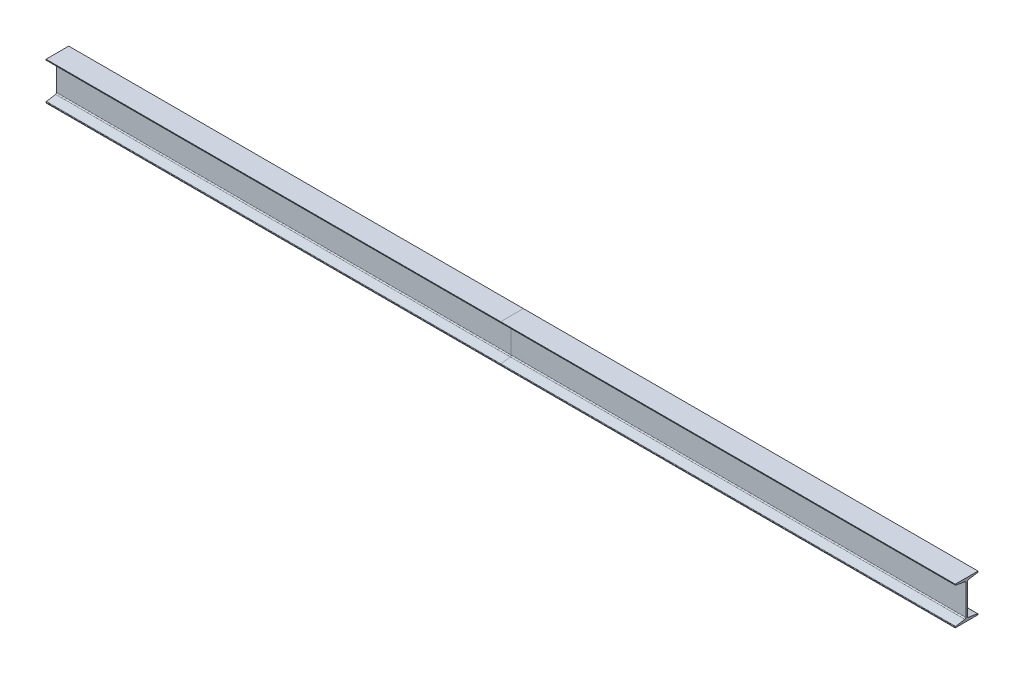
SolidWorks part; units mm, degrees
ref_plane "Front Plane" through (0, 0, 0) normal (0, 0, 1) x (1, 0, 0)
ref_plane "Top Plane" through (0, 0, 0) normal (0, 1, 0) x (1, 0, 0)
ref_plane "Right Plane" through (0, 0, 0) normal (1, 0, 0) x (0, 0, -1)
sketch "Sketch1" plane through (0, 0, 0) normal (0, 0, 1) x (1, 0, 0)
  line L0 (0, 0) -> (3048, 0)
  line L1 (3048, 0) -> (6096, 0)
  point P3 (4572, 0)
  dimension "D1" = 3048
  dimension "D2" = 6096
other "Structural Member1"
ref_plane "Plane1" through (0, 0, 0) normal (1, 0, 0) x (0, 0, 1)
sketch "Sketch11" plane through (0, 0, 0) normal (1, 0, 0) x (0, 0, 1)
  line L0 (-76.2, -127) -> (-76.2, -122.8792)
  line L1 (-73.4409, -119.6222) -> (-11.9134, -109.3669)
  line L2 (-5.334, -101.6) -> (-5.334, 101.6)
  line L3 (-11.9134, 109.3669) -> (-73.4409, 119.6222)
  line L4 (-76.2, 122.8792) -> (-76.2, 127)
  line L5 (-76.2, 127) -> (76.2, 127)
  line L6 (76.2, 127) -> (76.2, 122.8792)
  line L7 (73.4409, 119.6222) -> (11.9134, 109.3669)
  line L8 (5.334, 101.6) -> (5.334, -101.6)
  line L9 (11.9134, -109.3669) -> (73.4409, -119.6222)
  line L10 (76.2, -122.8792) -> (76.2, -127)
  line L11 (76.2, -127) -> (-76.2, -127)
  line L15 (-5.334, 0) -> (5.334, 0) construction
  arc A0 (-11.9134, -109.3669) -> (-5.334, -101.6) centre (-13.208, -101.6) ccw
  arc A1 (-5.334, 101.6) -> (-11.9134, 109.3669) centre (-13.208, 101.6) ccw
  arc A2 (11.9134, 109.3669) -> (5.334, 101.6) centre (13.208, 101.6) ccw
  arc A3 (5.334, -101.6) -> (11.9134, -109.3669) centre (13.208, -101.6) ccw
  arc A4 (-73.4409, 119.6222) -> (-76.2, 122.8792) centre (-72.898, 122.8792) cw
  arc A5 (73.4409, 119.6222) -> (76.2, 122.8792) centre (72.898, 122.8792) ccw
  arc A6 (-76.2, -122.8792) -> (-73.4409, -119.6222) centre (-72.898, -122.8792) cw
  arc A7 (76.2, -122.8792) -> (73.4409, -119.6222) centre (72.898, -122.8792) ccw
  point P1 (0, 127)
  point P8 (0, -127)
  point P21 (0, 0)
  point P34 (0, 0)
  dimension "D7" = 9.463
  dimension "RI" = 7.874
  dimension "D2" = 3.302
  dimension "BF" = 152.4
  dimension "DEPTH" = 254
  dimension "TW" = 10.668
  dimension "D1" = 203.2
ref_point "Point1"
equation "\"3.5903inx2\"=3.5903"
